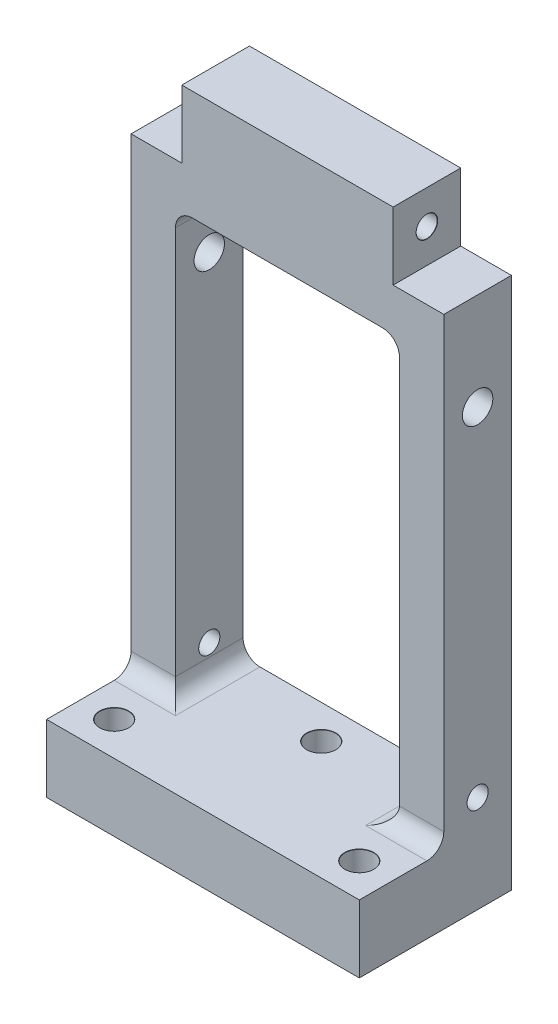
SolidWorks part; units mm, degrees
ref_plane "Front Plane" through (0, 0, 0) normal (0, 0, 1) x (1, 0, 0)
ref_plane "Top Plane" through (0, 0, 0) normal (0, 1, 0) x (1, 0, 0)
ref_plane "Right Plane" through (0, 0, 0) normal (1, 0, 0) x (0, 0, -1)
sketch "Sketch1" plane through (0, 0, 0) normal (0, 0, 1) x (1, 0, 0)
  line L0 (-13.4164, 3) -> (53.0006, 3) construction
  line L1 (-18.5, 0) -> (18.5, 0)
  line L2 (-18.5, 0) -> (-18.5, 63)
  line L3 (-18.5, 63) -> (18.5, 63)
  line L4 (18.5, 0) -> (18.5, 63)
  line L5 (-13.4164, 43) -> (50.705, 43) construction
  point P9 (0, 0)
  dimension "D1" = 37
  dimension "D2" = 3
  dimension "D3" = 20
  dimension "D4" = 40
extrude "Boss-Extrude1" add sketch "Sketch1" along normal blind 8
sketch "Sketch2" plane through (-18.5, 0, 0) normal (-1, 0, 0) x (0, 0, 1)
  line L0 (4, 63) -> (4, 0) construction
  line L1 (8, 63) -> (0, 63) construction
  line L2 (8, 0) -> (0, 0) construction
  line L3 (-33.1577, 31.5) -> (34.8767, 31.5) construction
  circle A0 centre (4, 51.5) radius 1
  circle A1 centre (4, 11.5) radius 1
  dimension "D1" = 2
  dimension "D3" = 2
  dimension "D2" = 40
extrude "Cut-Extrude1" cut sketch "Sketch2" against normal blind 10
mirror "Mirror1" about plane through (0, 0, 0) normal (1, 0, 0) of "Cut-Extrude1"
sketch "Sketch3" plane through (-18.5, 0, 0) normal (-1, 0, 0) x (0, 0, 1)
  line L1 (8, 0) -> (18, 0)
  line L2 (8, 0) -> (8, 8)
  line L3 (8, 8) -> (18, 8)
  line L4 (18, 0) -> (18, 8)
  dimension "D1" = 10
  dimension "D2" = 8
extrude "Boss-Extrude2" add sketch "Sketch3" against normal up to surface (37 mm away) up to face at (18.5, 51.5, 5)
sketch "Sketch4" plane through (0, 0, 8) normal (0, 0, 1) x (1, 0, 0)
  line L1 (-13.25, 58) -> (13.25, 58)
  line L2 (-13.25, 58) -> (-13.25, 8)
  line L3 (-13.25, 8) -> (13.25, 8)
  line L4 (13.25, 58) -> (13.25, 8)
  line L6 (18.5, 63) -> (-18.5, 63) construction
  line L8 (18.5, 8) -> (-18.5, 8) construction
  point P4 (0, 8)
  dimension "D1" = 26.5
  dimension "D3" = 5
extrude "Cut-Extrude2" cut sketch "Sketch4" against normal up to next
sketch "Sketch5" plane through (0, 8, 0) normal (0, 1, 0) x (1, 0, 0)
  line L0 (-29.6837, -14) -> (27.2943, -14) construction
  line L1 (0, 6.8821) -> (0, -27.3945) construction
  line L2 (-18.5, -18) -> (-18.5, -8) construction
  line L3 (18.5, -18) -> (-18.5, -18) construction
  line L4 (18.5, 0) -> (-18.5, 0) construction
  point P0 (-14.5, -14)
  point P1 (14.5, -14)
  point P2 (0, -4)
  dimension "D1" = 4
  dimension "D2" = 4
  dimension "D3" = 4
hole_wizard "M3 Clearance Hole1" positions "Sketch6" profile "Sketch7" hole size "M3" standard "ANSI Metric" end condition through all
sketch "Sketch6" plane through (0, 8, 0) normal (0, 1, 0) x (1, 0, 0)
  point P0 (-14.5, -14)
  point P3 (14.5, -14)
  point P6 (0, -4)
sketch "Sketch7" plane through (-14.5, 8, 14) normal (1, 0, 0) x (0, 0, 1)
  line L0 (0, 0) -> (0, 8)
  line L1 (0, 8) -> (1.725, 8)
  line L2 (1.7, 7.975) -> (1.7, 0.025)
  line L3 (1.7, 0.025) -> (1.725, 0)
  line L5 (1.725, 0) -> (0, 0)
  line L6 (-1.7, 0.025) -> (-1.725, 0) construction
  line L7 (1.725, 8) -> (1.7, 7.975)
  line L8 (-1.725, 8) -> (-1.7, 7.975) construction
  line L11 (0, -6.35) -> (0, 107.95) construction
  dimension "Thru Hole Dia." = 3.4
  dimension "Thru Hole Depth" = 8
  dimension "Near C'Sink Dia." = 3.45
  dimension "Near C'Sink Angle" = 90
  dimension "Far C'Sink Dia." = 3.45
  dimension "Far C'Sink Angle" = 90
fillet "Fillet1" radius 2 6 edges at (-15.875, 8, 8) (-13.25, 8, 4) (-13.25, 58, 4) (13.25, 58, 4) (15.875, 8, 8) (13.25, 8, 4)
sketch "Sketch8" plane through (0, 0, 0) normal (0, 0, -1) x (-1, 0, 0)
  line L0 (-18.5, 63) -> (18.5, 63) construction
  line L1 (12.5, 63) -> (-12.5, 63)
  line L2 (12.5, 63) -> (12.5, 71)
  line L3 (12.5, 71) -> (-12.5, 71)
  line L4 (-12.5, 63) -> (-12.5, 71)
  line L5 (18.5, 63) -> (18.5, 0) construction
  point P6 (0, 71)
  dimension "D1" = 6
  dimension "D2" = 8
extrude "Boss-Extrude3" add sketch "Sketch8" against normal up to surface (8 mm away) up to face at (0, 39.4828, 8)
sketch "Sketch9" plane through (-12.5, 0, 0) normal (-1, 0, 0) x (0, 0, 1)
  line L0 (0, 71) -> (8, 63) construction
  circle A0 centre (4, 67) radius 1
  point P6 (4, 67)
  dimension "D1" = 2
extrude "Cut-Extrude3" cut sketch "Sketch9" against normal blind 5
mirror "Mirror2" about plane through (0, 0, 0) normal (1, 0, 0) of "Cut-Extrude3"
hole_wizard "Tap Drill for M3x0.5 Tap1" positions "Sketch10" profile "Sketch11" hole size "M3x0.5" standard "ANSI Metric" end condition through all
sketch "Sketch10" plane through (-18.5, 0, 0) normal (-1, 0, 0) x (0, 0, 1)
  point P0 (4, 11.5)
sketch "Sketch11" plane through (-18.5, 11.5, 4) normal (0, 1, 0) x (0, 0, 1)
  line L0 (0, 0) -> (0, 37)
  line L1 (0, 37) -> (1.25, 37)
  line L2 (1.25, 37) -> (1.25, 0.025)
  line L3 (1.25, 0.025) -> (1.275, 0)
  line L5 (1.275, 0) -> (0, 0)
  line L6 (-1.25, 0.025) -> (-1.275, 0) construction
  line L11 (0, -6.35) -> (0, 107.95) construction
  dimension "Thru Hole Dia." = 2.5
  dimension "Thru Hole Depth" = 37
  dimension "Near C'Sink Dia." = 2.55
  dimension "Near C'Sink Angle" = 90
hole_wizard "M3 Clearance Hole2" positions "Sketch12" profile "Sketch13" hole size "M3" standard "ANSI Metric" end condition through all
sketch "Sketch12" plane through (-18.5, 0, 0) normal (-1, 0, 0) x (0, 0, 1)
  point P0 (4, 51.5)
sketch "Sketch13" plane through (-18.5, 51.5, 4) normal (0, 1, 0) x (0, 0, 1)
  line L0 (0, 0) -> (0, 37)
  line L1 (0, 37) -> (1.8, 37)
  line L2 (1.8, 37) -> (1.8, 0.025)
  line L3 (1.8, 0.025) -> (1.825, 0)
  line L5 (1.825, 0) -> (0, 0)
  line L6 (-1.8, 0.025) -> (-1.825, 0) construction
  line L11 (0, -6.35) -> (0, 107.95) construction
  dimension "Thru Hole Dia." = 3.6
  dimension "Thru Hole Depth" = 37
  dimension "Near C'Sink Dia." = 3.65
  dimension "Near C'Sink Angle" = 90
hole_wizard "Tap Drill for M3x0.5 Tap2" positions "Sketch14" profile "Sketch15" hole size "M3x0.5" standard "ANSI Metric"
sketch "Sketch14" plane through (-12.5, 0, 0) normal (-1, 0, 0) x (0, 0, 1)
  point P0 (4, 67)
sketch "Sketch15" plane through (-12.5, 67, 4) normal (0, 1, 0) x (0, 0, 1)
  line L0 (0, 0) -> (0, 20.7511)
  line L1 (0, 20.7511) -> (1.25, 20)
  line L2 (1.25, 20) -> (1.25, 0.025)
  line L3 (1.25, 0.025) -> (1.275, 0)
  line L5 (1.275, 0) -> (0, 0)
  line L6 (-1.25, 0.025) -> (-1.275, 0) construction
  line L10 (0, 20.7511) -> (-1.25, 20) construction
  line L11 (0, -6.35) -> (0, 107.95) construction
  dimension "Hole Dia." = 2.5
  dimension "Hole Depth" = 20
  dimension "Near C'Sink Dia." = 2.55
  dimension "Near C'Sink Angle" = 90
  dimension "Drill Angle" = 118
mirror "Mirror3" about plane through (0, 0, 0) normal (1, 0, 0) of "Tap Drill for M3x0.5 Tap2"
